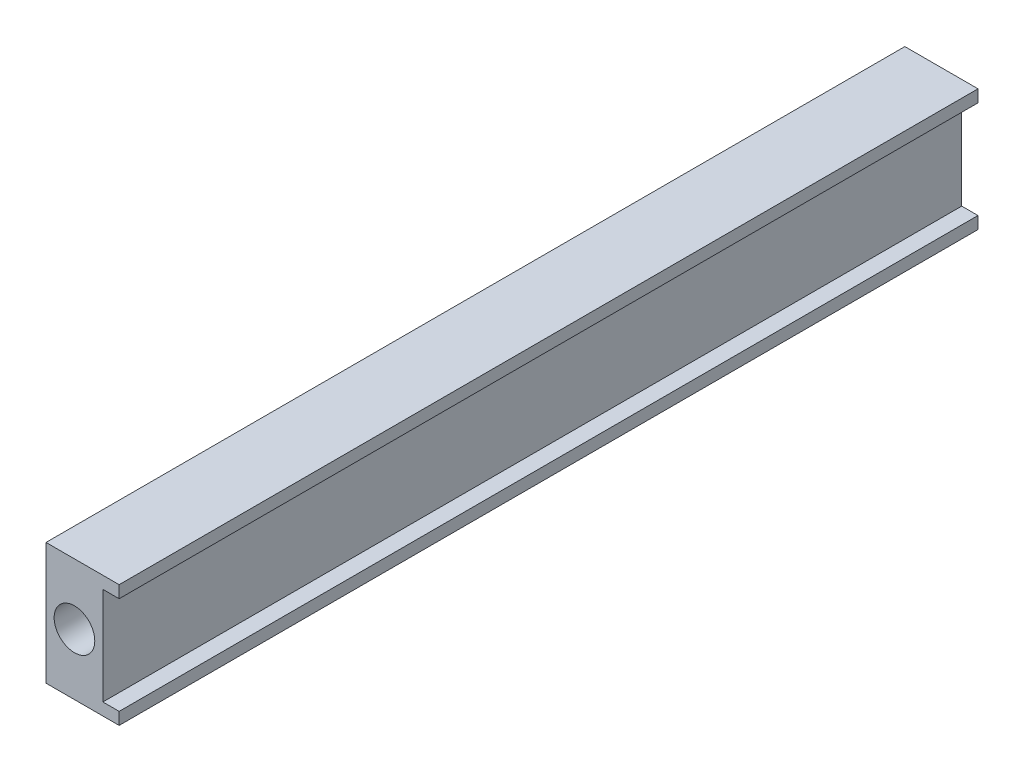
SolidWorks part; units mm, degrees
ref_plane "Front Plane" through (0, 0, 0) normal (0, 0, 1) x (1, 0, 0)
ref_plane "Top Plane" through (0, 0, 0) normal (0, 1, 0) x (1, 0, 0)
ref_plane "Right Plane" through (0, 0, 0) normal (1, 0, 0) x (0, 0, -1)
sketch "Sketch2" plane through (0, 0, 0) normal (0, 0, 1) x (1, 0, 0)
  line L1 (0, 0) -> (18, 0)
  line L2 (0, 0) -> (0, -30)
  line L3 (0, -30) -> (18, -30)
  line L4 (18, 0) -> (18, -30)
  dimension "D1" = 30
  dimension "D2" = 18
extrude "Boss-Extrude1" add sketch "Sketch2" against normal blind 211.341
sketch "Sketch3" plane through (0, 0, 0) normal (0, 0, 1) x (1, 0, 0)
  line L0 (18, -30) -> (18, 0) construction
  line L1 (18, -3) -> (14, -3)
  line L2 (18, -3) -> (18, -27)
  line L3 (18, -27) -> (14, -27)
  line L4 (14, -3) -> (14, -27)
  line L5 (0, -30) -> (18, -30) construction
  dimension "D1" = 24
  dimension "D2" = 3
  dimension "D3" = 4
extrude "Cut-Extrude1" cut sketch "Sketch3" against normal blind 1000
sketch "Sketch4" plane through (0, 0, 0) normal (0, 0, 1) x (1, 0, 0)
  line L0 (0, 0) -> (0, -30) construction
  line L2 (18, 0) -> (0, 0) construction
  circle A0 centre (7, -15) radius 5
  dimension "D1" = 10
  dimension "D2" = 7
  dimension "D3" = 15
extrude "Cut-Extrude2" cut sketch "Sketch4" against normal blind 25
sketch "Sketch5" plane through (0, 0, -211.341) normal (0, 0, -1) x (-1, 0, 0)
  line L0 (0, 0) -> (0, -30) construction
  line L5 (-18, 0) -> (0, 0) construction
  circle A0 centre (-7, -15) radius 5
  dimension "D1" = 10
  dimension "D2" = 7
  dimension "D3" = 15
extrude "Cut-Extrude3" cut sketch "Sketch5" against normal blind 25
